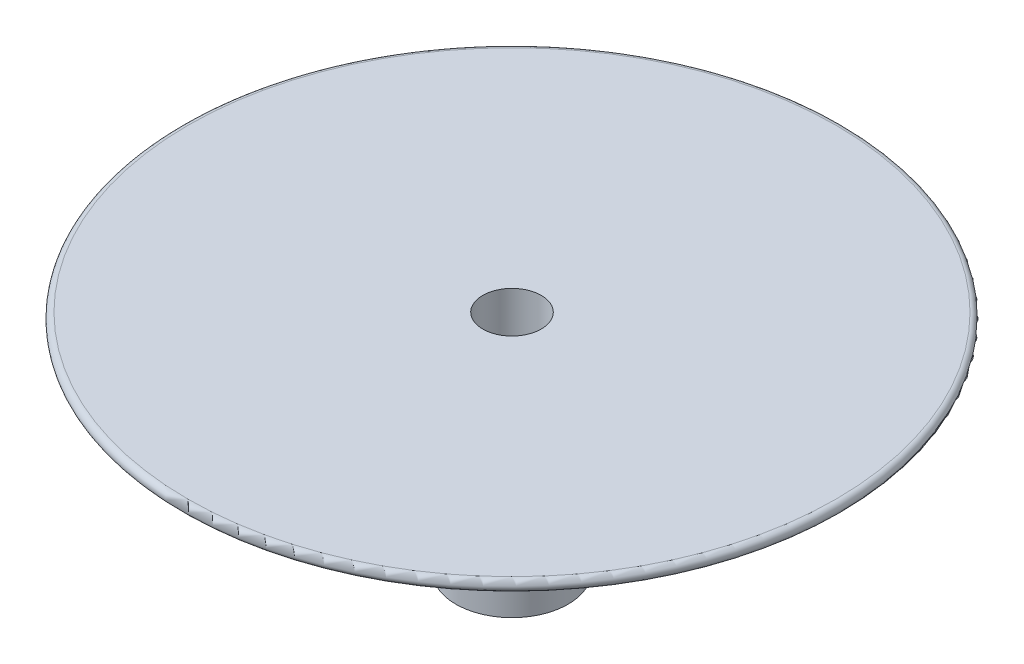
SolidWorks part; units mm, degrees
ref_plane "Front Plane" through (0, 0, 0) normal (0, 0, 1) x (1, 0, 0)
ref_plane "Top Plane" through (0, 0, 0) normal (0, 1, 0) x (1, 0, 0)
ref_plane "Right Plane" through (0, 0, 0) normal (1, 0, 0) x (0, 0, -1)
sketch "Sketch1" plane through (0, 0, 0) normal (0, 0, 1) x (1, 0, 0)
  line L0 (0, 10) -> (0, 0)
  line L1 (0, 10) -> (30.3313, 10)
  line L2 (0, 0) -> (0, -10)
  line L3 (0, -10) -> (5, -10)
  line L4 (5, -10) -> (5, 0)
  arc A1 (5, 0) -> (30.3313, 10) centre (0, 49.7494) ccw
  point P0 (0, -2.7157)
  dimension "D1" = 50
  dimension "D2" = 10
  dimension "D3" = 5
  dimension "D4" = 10
revolve "Revolve1" add sketch "Sketch1" angle 360 about L0
sketch "Sketch2" plane through (0, 10, 0) normal (0, 1, 0) x (1, 0, 0)
  circle A0 centre (0, 0) radius 2.6
  dimension "D1" = 5.2
extrude "Cut-Extrude1" cut sketch "Sketch2" against normal through all
fillet "Fillet1" radius 0.5 1 edges at (-30.3313, 10, 0)
